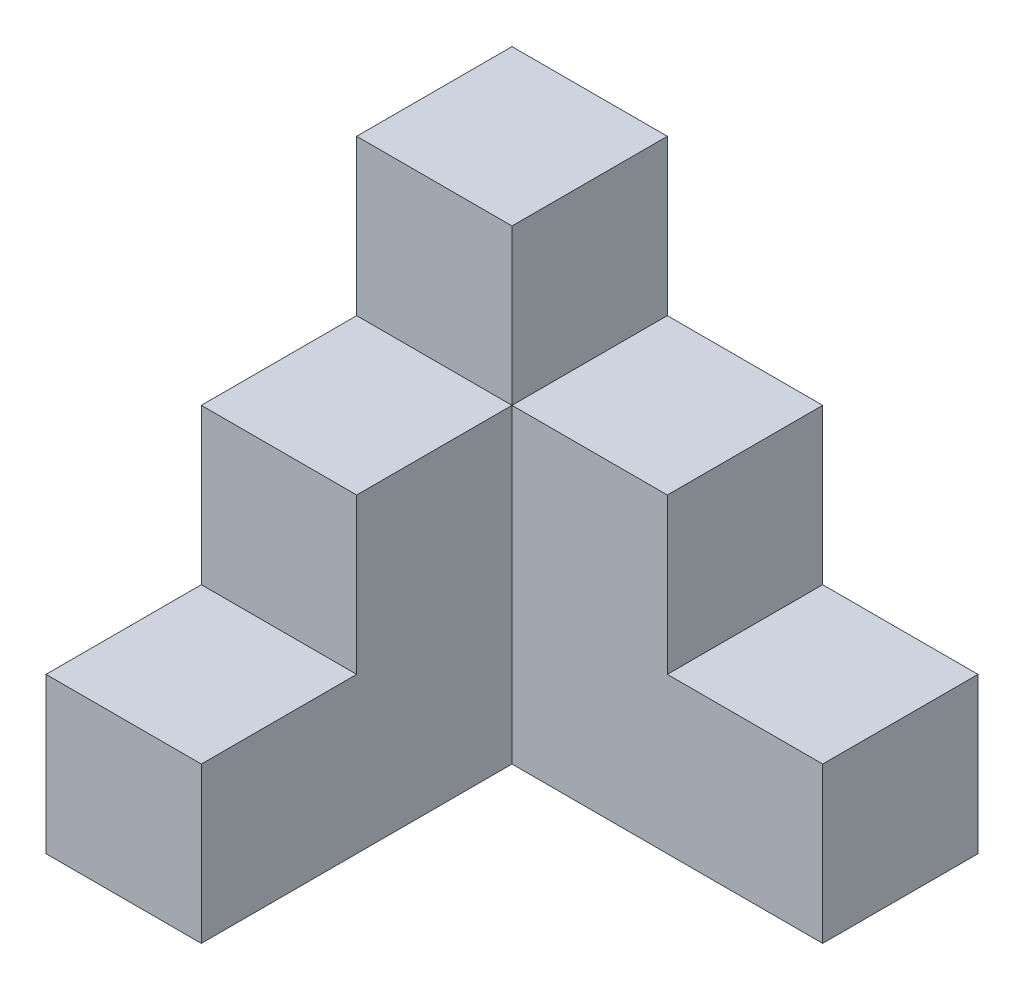
SolidWorks part; units mm, degrees
ref_plane "Alzado" through (0, 0, 0) normal (0, 0, 1) x (1, 0, 0)
ref_plane "Planta" through (0, 0, 0) normal (0, 1, 0) x (1, 0, 0)
ref_plane "Vista lateral" through (0, 0, 0) normal (1, 0, 0) x (0, 0, -1)
sketch "Croquis2" plane through (0, 0, 0) normal (0, 1, 0) x (1, 0, 0)
  line L1 (-232.2479, -236.4396) -> (-222.2479, -236.4396)
  line L2 (-232.2479, -236.4396) -> (-232.2479, -266.4396)
  line L3 (-232.2479, -266.4396) -> (-222.2479, -266.4396)
  line L4 (-222.2479, -246.4396) -> (-222.2479, -266.4396)
  line L11 (-222.2479, -236.4396) -> (-202.2479, -236.4396)
  line L17 (-202.2479, -236.4396) -> (-202.2479, -246.4396)
  line L18 (-202.2479, -246.4396) -> (-222.2479, -246.4396)
  point P4 (-227.2479, -251.4396)
  point P9 (-212.2479, -241.4396)
  dimension "D1" = 30
  dimension "D2" = 10
extrude "Saliente-Extruir1" add sketch "Croquis2" along normal blind 10
sketch "Croquis3" plane through (0, 10, 0) normal (0, 1, 0) x (1, 0, 0)
  line L0 (-222.2479, -236.4396) -> (-212.2479, -236.4396)
  line L1 (-232.2479, -236.4396) -> (-222.2479, -236.4396)
  line L2 (-232.2479, -236.4396) -> (-232.2479, -256.4396)
  line L3 (-232.2479, -256.4396) -> (-222.2479, -256.4396)
  line L4 (-222.2479, -246.4396) -> (-222.2479, -256.4396)
  line L7 (-202.2479, -236.4396) -> (-232.2479, -236.4396) construction
  line L8 (-212.2479, -236.4396) -> (-212.2479, -246.4396)
  line L9 (-212.2479, -246.4396) -> (-222.2479, -246.4396)
  point P4 (-227.2479, -246.4396)
  dimension "D1" = 10
extrude "Saliente-Extruir2" add sketch "Croquis3" along normal blind 10
sketch "Croquis4" plane through (0, 20, 0) normal (0, 1, 0) x (1, 0, 0)
  line L1 (-232.2479, -236.4396) -> (-222.2479, -236.4396)
  line L2 (-232.2479, -236.4396) -> (-232.2479, -246.4396)
  line L3 (-232.2479, -246.4396) -> (-222.2479, -246.4396)
  line L4 (-222.2479, -236.4396) -> (-222.2479, -246.4396)
  line L5 (-232.2479, -236.4396) -> (-222.2479, -246.4396) construction
  line L6 (-232.2479, -246.4396) -> (-222.2479, -236.4396) construction
  point P4 (-227.2479, -241.4396)
extrude "Saliente-Extruir3" add sketch "Croquis4" along normal blind 10
